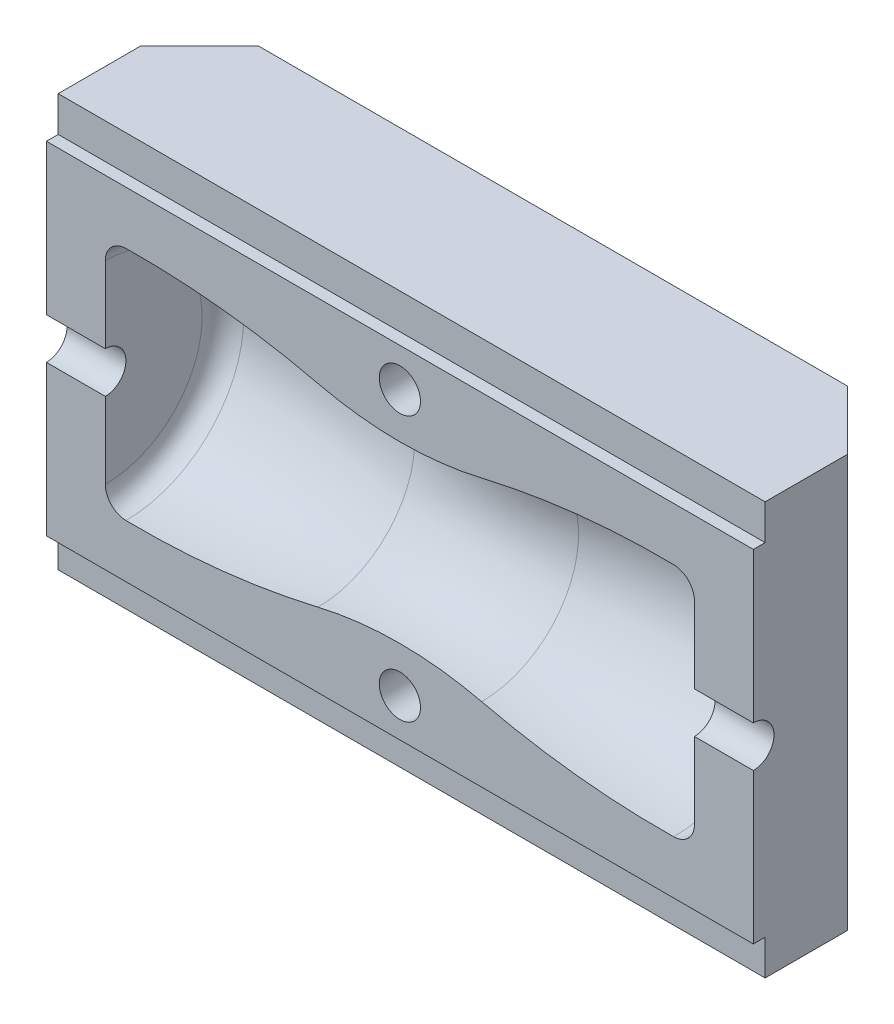
SolidWorks part; units mm, degrees
ref_plane "Front Plane" through (0, 0, 0) normal (0, 0, 1) x (1, 0, 0)
ref_plane "Top Plane" through (0, 0, 0) normal (0, 1, 0) x (1, 0, 0)
ref_plane "Right Plane" through (0, 0, 0) normal (1, 0, 0) x (0, 0, -1)
sketch "Sketch1" plane through (0, 0, 0) normal (0, 0, 1) x (1, 0, 0)
  line L1 (-30, 17.5) -> (30, 17.5)
  line L2 (-30, 17.5) -> (-30, -17.5)
  line L3 (-30, -17.5) -> (30, -17.5)
  line L4 (30, 17.5) -> (30, -17.5)
  line L5 (-30, 17.5) -> (30, -17.5) construction
  line L6 (-30, -17.5) -> (30, 17.5) construction
  point P0 (0, 0)
  dimension "D1" = 35
  dimension "D2" = 60
extrude "Boss-Extrude1" add sketch "Sketch1" along normal blind 13
sketch "Sketch2" plane through (0, 0, 13) normal (0, 0, 1) x (1, 0, 0)
  line L0 (-30, 0) -> (30, 0) construction
  line L1 (-30, 17.5) -> (-30, -17.5) construction
  line L2 (30, -17.5) -> (30, 17.5) construction
  line L3 (-25, 0) -> (-25, 8.2181)
  line L4 (-6.9483, 8.2181) -> (6.9483, 8.2181) construction
  line L5 (0, 8.2181) -> (0, 0) construction
  line L6 (25, 8.2181) -> (25, 0)
  line L7 (25, 0) -> (-25, 0)
  line L8 (-25, 8.2181) -> (25, 8.2181) construction
  line L9 (23.2433, 10) -> (-23.2433, 10) construction
  arc A0 (-25, 8.2181) -> (-23.2433, 10) centre (-23.2179, 8.2181) cw
  arc A1 (-23.2433, 10) -> (-6.9483, 8.2181) centre (-22.2956, -56.7322) cw
  arc A2 (-6.9483, 8.2181) -> (6.9483, 8.2181) centre (0, 37.6237) ccw
  arc A3 (6.9483, 8.2181) -> (23.2433, 10) centre (22.2956, -56.7322) cw
  arc A4 (23.2433, 10) -> (25, 8.2181) centre (23.2179, 8.2181) cw
  point P21 (-20.8843, 10)
  point P23 (-6.9483, 8.2181)
  dimension "D3" = 1.7821
  dimension "D1" = 50
  dimension "D2" = 10
revolve "Cut-Revolve1" cut sketch "Sketch2" angle 360 about L7
sketch "Sketch3" plane through (30, 0, 0) normal (1, 0, 0) x (0, 0, -1)
  line L0 (-13, -17.5) -> (-13, 17.5) construction
  circle A0 centre (-13, 0) radius 1.75
  dimension "D1" = 3.5
extrude "Cut-Extrude1" cut sketch "Sketch3" against normal through all both
sketch "Sketch4" plane through (0, 0, 13) normal (0, 0, 1) x (1, 0, 0)
  line L0 (30, 1.75) -> (30, 17.5) construction
  line L1 (-30, 17.5) -> (30, 17.5)
  line L2 (-30, 17.5) -> (-30, 14.5)
  line L3 (-30, 14.5) -> (30, 14.5)
  line L4 (30, 17.5) -> (30, 14.5)
  line L5 (-30, -1.75) -> (-30, -17.5) construction
  line L6 (30, -17.5) -> (-30, -17.5)
  line L7 (30, -17.5) -> (30, -14.5)
  line L8 (30, -14.5) -> (-30, -14.5)
  line L9 (-30, -17.5) -> (-30, -14.5)
  dimension "D1" = 3
extrude "Cut-Extrude2" cut sketch "Sketch4" against normal blind 1
sketch "Sketch5" plane through (0, 0, 13) normal (0, 0, 1) x (1, 0, 0)
  line L0 (0, 11.25) -> (0, -11.25) construction
  circle A0 centre (0, 11.25) radius 1.75
  circle A1 centre (0, -11.25) radius 1.75
  dimension "D1" = 3.5
  dimension "D2" = 22.5
extrude "Cut-Extrude3" cut sketch "Sketch5" against normal through all
chamfer "Chamfer1" distance 5 angle 45 2 edges at (30, 0, 0) (-30, 0, 0)
sketch "Sketch6" plane through (0, 0, 0) normal (0, 0, -1) x (-1, 0, 0)
  circle A8 centre (0, 11.25) radius 3.75
  circle A9 centre (0, 11.25) radius 3.75
  circle A12 centre (0, -11.25) radius 3.75
  dimension "D1" = 2
extrude "Cut-Extrude4" cut sketch "Sketch6" against normal blind 7
chamfer "Chamfer2" distance 0.5 angle 45 6 edges at (-1.75, 11.25, 7) (-3.75, 11.25, 7) (-1.75, -11.25, 7) (-3.75, -11.25, 7) (-3.75, -11.25, 0) (-3.75, 11.25, 0)
